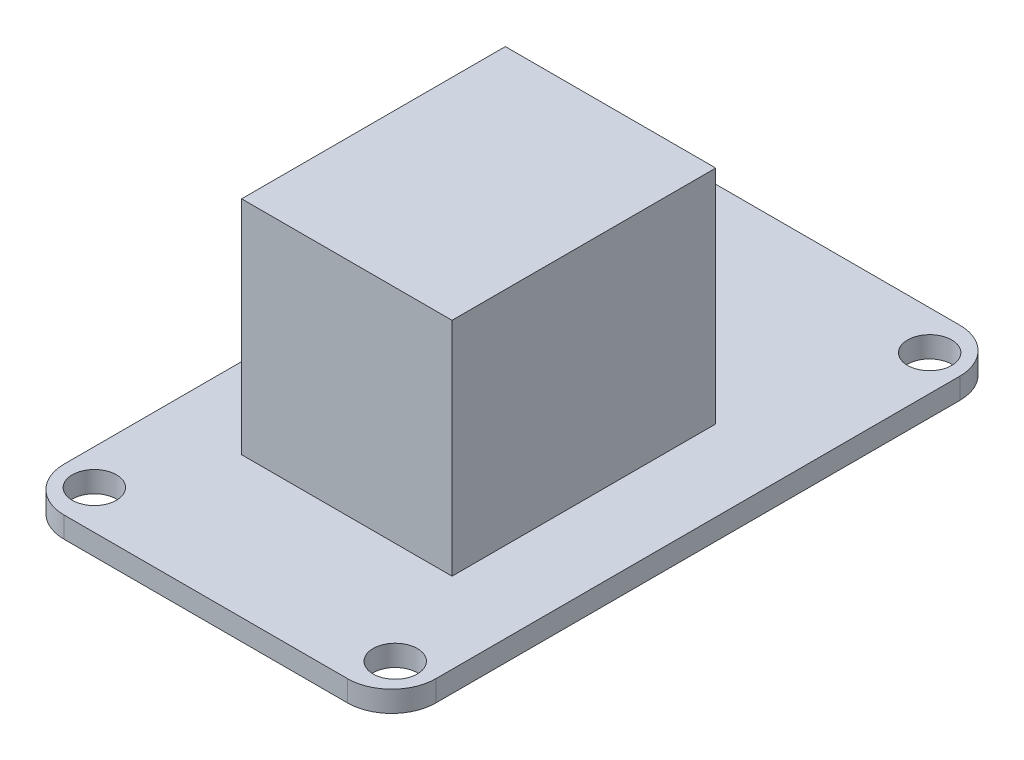
SolidWorks part; units mm, degrees
ref_plane "Front Plane" through (0, 0, 0) normal (0, 0, 1) x (1, 0, 0)
ref_plane "Top Plane" through (0, 0, 0) normal (0, 1, 0) x (1, 0, 0)
ref_plane "Right Plane" through (0, 0, 0) normal (1, 0, 0) x (0, 0, -1)
sketch "Sketch1" plane through (0, 0, 0) normal (0, 1, 0) x (1, 0, 0)
  line L1 (13.25, 21.825) -> (-13.25, 21.825)
  line L2 (13.25, 21.825) -> (13.25, -21.825)
  line L3 (13.25, -21.825) -> (-13.25, -21.825)
  line L4 (-13.25, 21.825) -> (-13.25, -21.825)
  line L5 (13.25, 21.825) -> (-13.25, -21.825) construction
  line L6 (13.25, -21.825) -> (-13.25, 21.825) construction
  point P0 (0, 0)
  dimension "D1" = 26.5
  dimension "D2" = 43.65
extrude "Boss-Extrude1" add sketch "Sketch1" along normal blind 1.5
fillet "Fillet1" radius 3.15 4 edges at (-13.25, 0.75, -21.825) (13.25, 0.75, -21.825) (13.25, 0.75, 21.825) (-13.25, 0.75, 21.825)
sketch "Sketch2" plane through (0, 1.5, 0) normal (0, 1, 0) x (1, 0, 0)
  line L0 (0, 21.825) -> (0, -21.825) construction
  line L1 (10.1, 21.825) -> (-10.1, 21.825) construction
  line L2 (-10.1, -21.825) -> (10.1, -21.825) construction
  line L3 (-13.25, 0) -> (13.25, 0) construction
  line L4 (-13.25, 18.675) -> (-13.25, -18.675) construction
  line L5 (13.25, -18.675) -> (13.25, 18.675) construction
  circle A0 centre (-10.725, 19.05) radius 1.575
  circle A1 centre (10.725, 19.05) radius 1.575
  circle A2 centre (10.725, -19.05) radius 1.575
  circle A3 centre (-10.725, -19.05) radius 1.575
  point P18 (0, 0)
  point P21 (0, 0)
  point P22 (0, 0)
  point P23 (0, 0)
  point P24 (0, 0)
  point P25 (0, 0)
  dimension "D1" = 3.15
  dimension "D2" = 41.25
  dimension "D3" = 24.6
extrude "Cut-Extrude1" cut sketch "Sketch2" against normal blind 1.5
sketch "Sketch3" plane through (0, 1.5, 0) normal (0, 1, 0) x (1, 0, 0)
  line L0 (10.1, 21.825) -> (-10.1, 21.825) construction
  line L1 (7.5, 7.025) -> (-7.5, 7.025)
  line L2 (7.5, 7.025) -> (7.5, -11.775)
  line L3 (7.5, -11.775) -> (-7.5, -11.775)
  line L4 (-7.5, 7.025) -> (-7.5, -11.775)
  line L5 (7.5, 7.025) -> (-7.5, -11.775) construction
  line L6 (7.5, -11.775) -> (-7.5, 7.025) construction
  point P0 (0, -2.375)
  point P5 (0, 0)
  dimension "D1" = 15
  dimension "D2" = 18.8
  dimension "D3" = 14.8
extrude "Boss-Extrude2" add sketch "Sketch3" along normal blind 15.8
